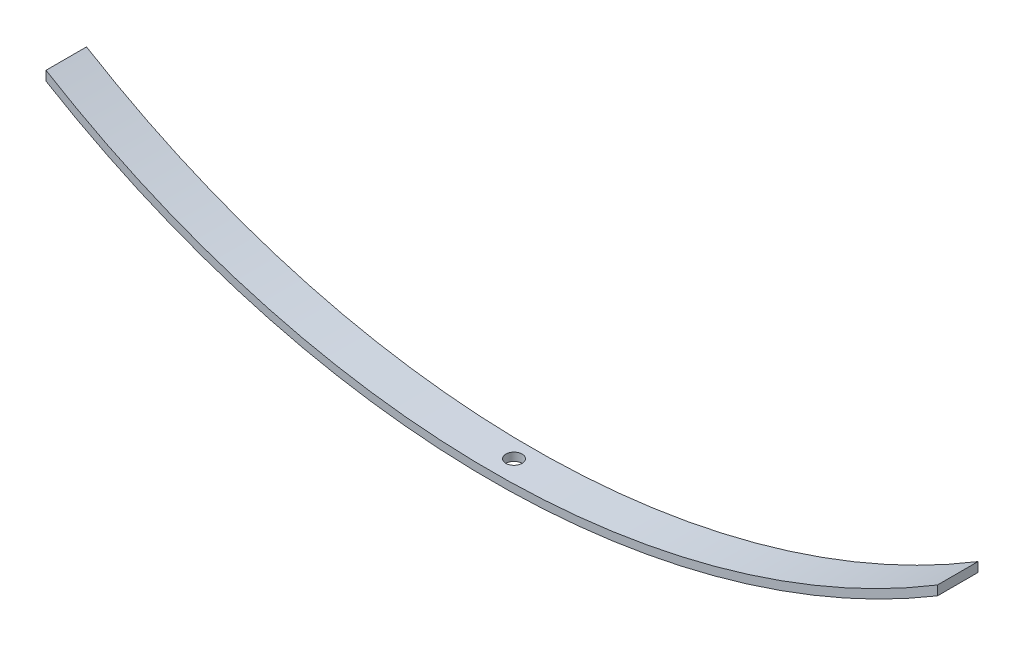
SolidWorks part; units mm, degrees
ref_plane "Front Plane" through (0, 0, 0) normal (0, 0, 1) x (1, 0, 0)
ref_plane "Top Plane" through (0, 0, 0) normal (0, 1, 0) x (1, 0, 0)
ref_plane "Right Plane" through (0, 0, 0) normal (1, 0, 0) x (0, 0, -1)
sketch "Sketch1" plane through (0, 0, 0) normal (0, 0, 1) x (1, 0, 0)
  line L0 (-550, -906.1457) -> (-550, -917.8235)
  line L1 (0, 0) -> (0, -3000.7365)
  line L2 (550, -906.1457) -> (550, -917.8235)
  arc A0 (-550, -906.1457) -> (550, -906.1457) centre (0, 0) ccw
  arc A1 (-550, -917.8235) -> (550, -917.8235) centre (0, 0) ccw
  point P7 (-550, -911.9846)
  dimension "D1" = 2120
  dimension "D2" = 2140
  dimension "D3" = 550
extrude "Boss-Extrude1" add sketch "Sketch1" along normal blind 50 contours A0 L2 A1 L0
sketch "Sketch3" plane through (0, 0, 0) normal (0, 1, 0) x (1, 0, 0)
  line L0 (0, 0) -> (0, -53.543) construction
  line L1 (550, 0) -> (-550, 0) construction
  circle A0 centre (0, -22.5) radius 10
  dimension "D1" = 20
  dimension "D2" = 22.5
extrude "Cut-Extrude1" cut sketch "Sketch3" against normal through all
